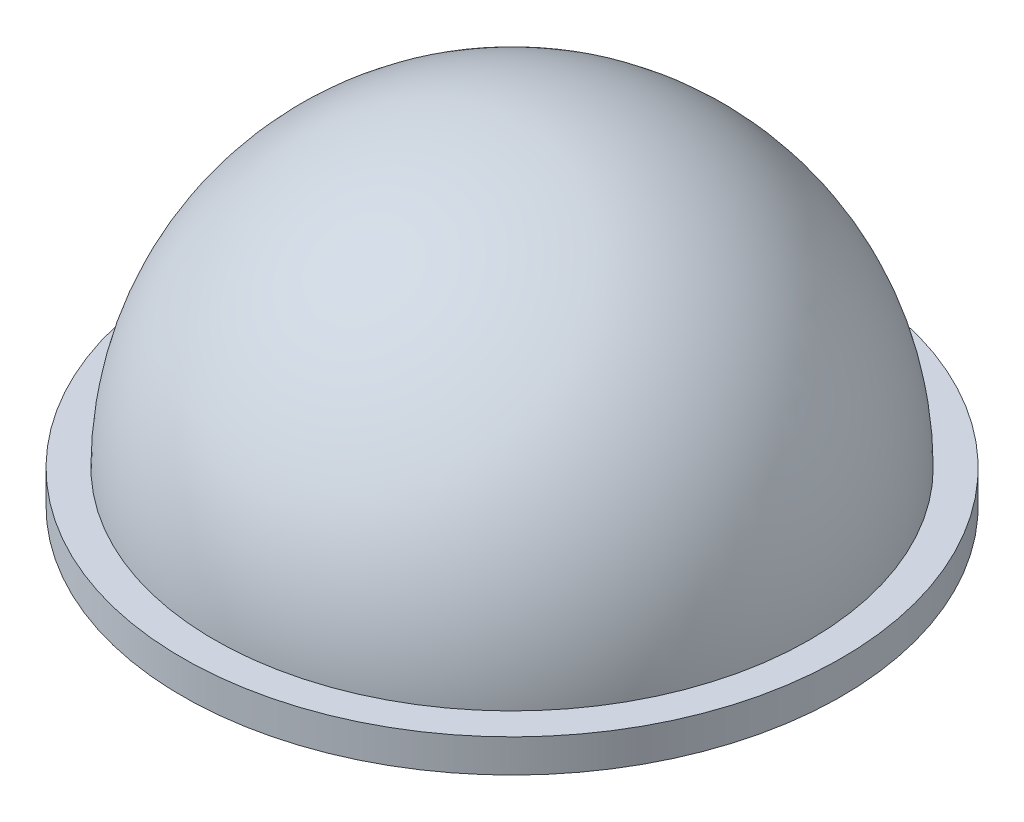
SolidWorks part; units mm, degrees
material "ABS PC"
ref_plane "前视基准面" through (0, 0, 0) normal (0, 0, 1) x (1, 0, 0)
ref_plane "上视基准面" through (0, 0, 0) normal (0, 1, 0) x (1, 0, 0)
ref_plane "右视基准面" through (0, 0, 0) normal (1, 0, 0) x (0, 0, -1)
sketch "草图1" plane through (0, 0, 0) normal (0, 0, 1) x (1, 0, 0)
  line L0 (45, 0) -> (49.8, 0)
  line L1 (40, 0) -> (40, -5)
  line L2 (40, -5) -> (49.8, -5)
  line L3 (49.8, -5) -> (49.8, 0)
  line L4 (0, 45) -> (0, 40)
  line L5 (0, 0) -> (0, 66.35) construction
  arc A0 (40, 0) -> (0, 40) centre (0, 0) ccw
  arc A1 (45, 0) -> (0, 45) centre (0, 0) ccw
  dimension "D1" = 40
  dimension "D2" = 45
  dimension "D3" = 49.8
  dimension "D4" = 5
  dimension "D5" = 5
revolve "旋转1" add sketch "草图1" angle 360 about L5
